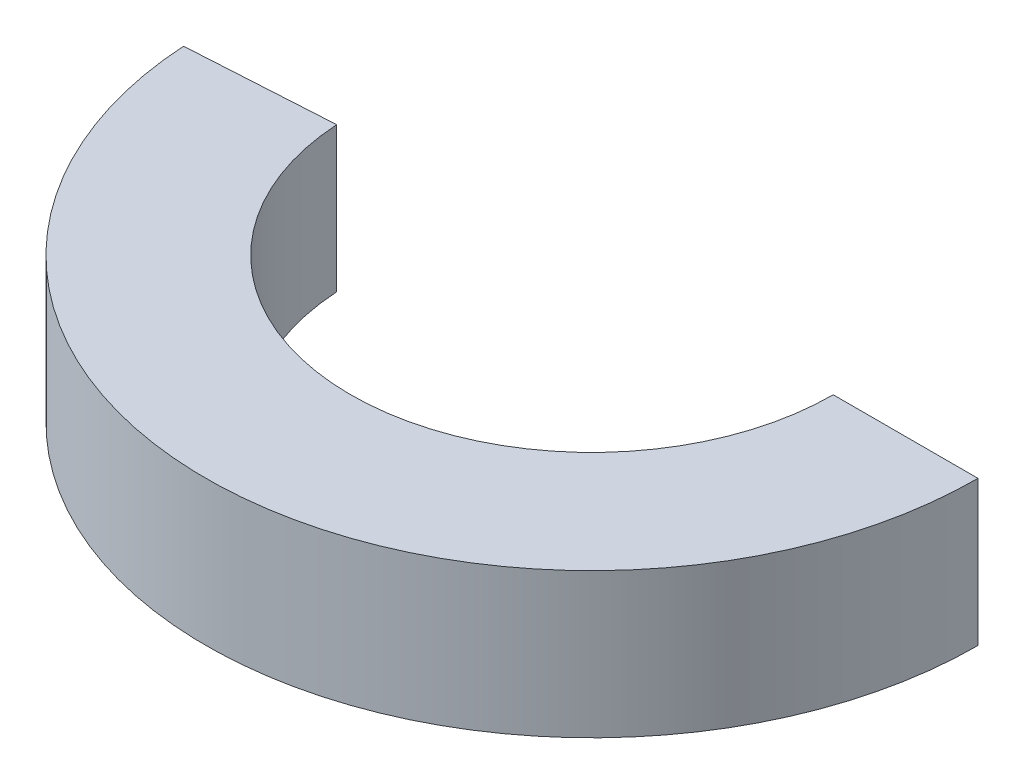
SolidWorks part; units mm, degrees
ref_plane "Front Plane" through (0, 0, 0) normal (0, 0, 1) x (1, 0, 0)
ref_plane "Top Plane" through (0, 0, 0) normal (0, 1, 0) x (1, 0, 0)
ref_plane "Right Plane" through (0, 0, 0) normal (1, 0, 0) x (0, 0, -1)
sketch "Sketch1" plane through (0, 0, 0) normal (0, 1, 0) x (1, 0, 0)
  line L0 (-39.9292, -2.3792) -> (0, 0)
  line L1 (0, 0) -> (40, 0)
  circle A0 centre (0, 0) radius 25
  circle A1 centre (0, 0) radius 40
  dimension "D1" = 15
  dimension "D2" = 80
  dimension "D3" = 176.59
extrude "Boss-Extrude1" add sketch "Sketch1" along normal blind 15 contours L0 A1 L1 A0
